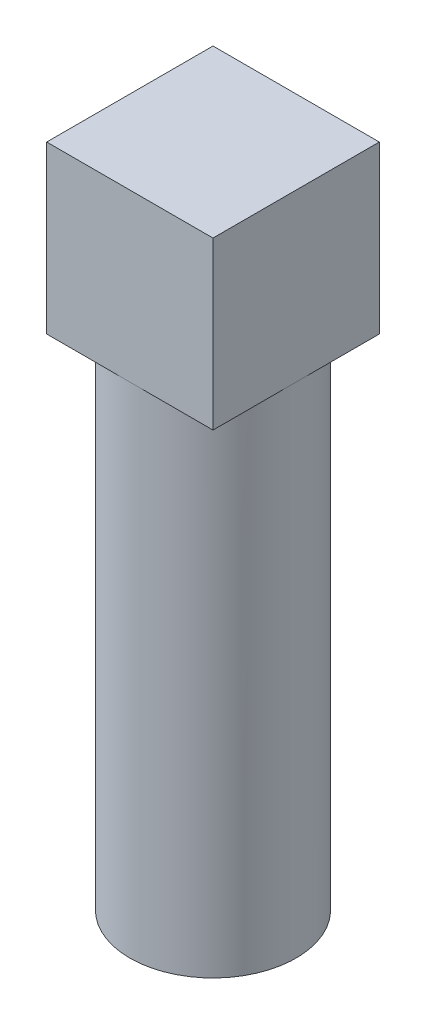
SolidWorks part; units mm, degrees
ref_plane "Plano frontal" through (0, 0, 0) normal (0, 0, 1) x (1, 0, 0)
ref_plane "Plano superior" through (0, 0, 0) normal (0, 1, 0) x (1, 0, 0)
ref_plane "Plano direito" through (0, 0, 0) normal (1, 0, 0) x (0, 0, -1)
sketch "Esboço1" plane through (0, 0, 0) normal (0, 1, 0) x (1, 0, 0)
  circle A0 centre (0, 0) radius 0.5
  dimension "D1" = 1
extrude "Ressalto-extrusão1" add sketch "Esboço1" along normal blind 4
sketch "Esboço2" plane through (0, 4, 0) normal (0, 1, 0) x (1, 0, 0)
  line L1 (0.5, 0.5) -> (-0.5, 0.5)
  line L2 (0.5, 0.5) -> (0.5, -0.5)
  line L3 (0.5, -0.5) -> (-0.5, -0.5)
  line L4 (-0.5, 0.5) -> (-0.5, -0.5)
  line L5 (0.5, 0.5) -> (-0.5, -0.5) construction
  line L6 (0.5, -0.5) -> (-0.5, 0.5) construction
  point P0 (0, 0)
  dimension "D1" = 1
  dimension "D2" = 1
extrude "Ressalto-extrusão2" add sketch "Esboço2" against normal blind 1
